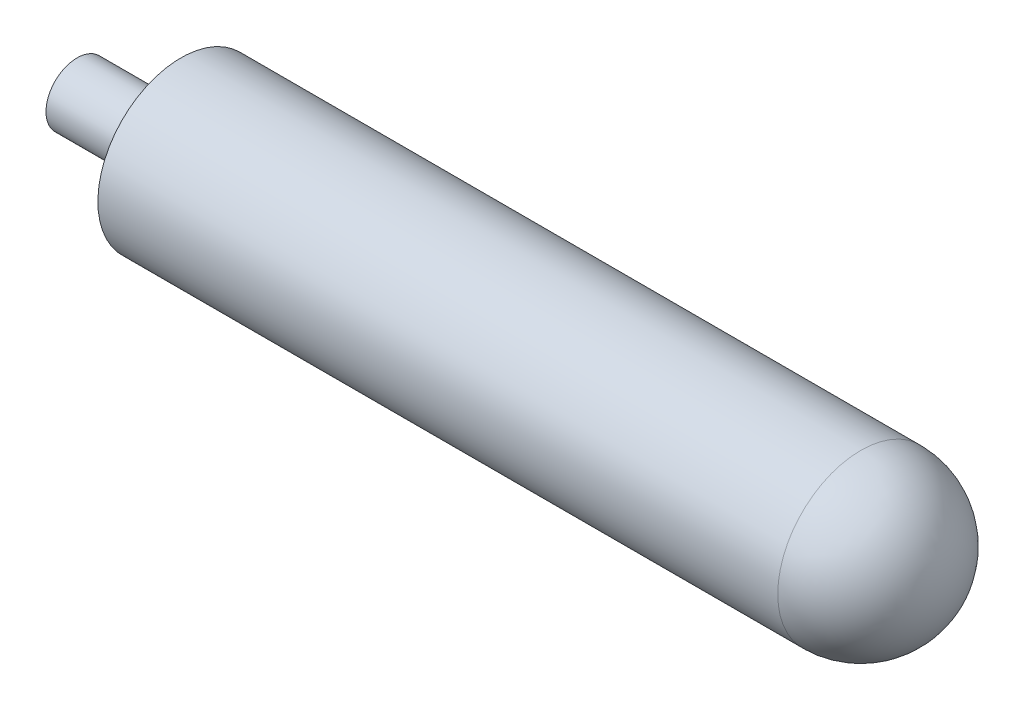
SolidWorks part; units mm, degrees
ref_plane "Front Plane" through (0, 0, 0) normal (0, 0, 1) x (1, 0, 0)
ref_plane "Top Plane" through (0, 0, 0) normal (0, 1, 0) x (1, 0, 0)
ref_plane "Right Plane" through (0, 0, 0) normal (1, 0, 0) x (0, 0, -1)
sketch "Sketch1" plane through (0, 0, 0) normal (0, 0, 1) x (1, 0, 0)
  line L0 (0, 0) -> (68, 0) construction
  line L1 (6.5, 0) -> (6.5, 3)
  line L2 (6.5, 3) -> (16.5, 3)
  line L3 (16.5, 3) -> (16.5, 8)
  line L4 (16.5, 8) -> (68, 8)
  line L5 (68, 8) -> (68, 0)
  line L6 (6.5, 0) -> (68, 0) construction
  line L7 (6.5, 0) -> (68, 0)
  point P8 (6.5, 1.5)
  point P10 (67.5075, 0)
  dimension "D1" = 6.5
  dimension "D2" = 16.5
  dimension "D3" = 68
  dimension "D4" = 3
  dimension "D5" = 8
revolve "Revolve1" add sketch "Sketch1" angle 360 about L7
sketch "Sketch2" plane through (0, 0, 0) normal (0, 0, 1) x (1, 0, 0)
  line L0 (0, 0) -> (109.6147, 0) construction
  line L1 (68, 0) -> (68, 8)
  line L2 (68, 8) -> (16.5, 8) construction
  line L5 (68, 8) -> (82, 8)
  line L7 (68, 0) -> (90, 0)
  arc A1 (82, 8) -> (90, 0) centre (82, 0) cw
  dimension "D3" = 8
  dimension "D1" = 68
  dimension "D2" = 82
revolve "Revolve2" add sketch "Sketch2" angle 360 about L0
equation "\"TipBracket: Turret Offset\"= 16mm"
equation "\"TipBracket: Axle Diameter\"= 6mm"
equation "\"TipBracket: Bearing Outer Diameter\"= 13mm'686ZZ"
equation "\"TipBracket: Bearing Width\"= 5mm'686ZZ"
equation "\"TipBracket: Bracket Thickness\"= 4mm"
equation "\"TipBracket: Socket Outer\"= \"Bracket: Arm Gap\" + 2 * \"Bracket: Clamp Wall\""
equation "\"TipBracket: Socket Cap\"= 3mm"
equation "\"TipBracket: Bearing Housing Wall Thicknes\"= 2.5mm"
equation "\"TipBracket: Bearing Boss Diameter\"= \"TipBracket: Bearing Outer Diameter\" + 2 * \"TipBracket: Bearing Housing Wall Thicknes\""
equation "\"TipBracket: Socket-Axle Distance\"= \"Bracket: Clamp Length\" + \"TipBracket: Bearing Boss Diameter\" / 2"
equation "\"Bracket: Arm Size\"= 10mm"
equation "\"Bracket: Arm Gap\"= \"Bracket: Arm Size\" + 0.2mm"
equation "\"Bracket: Clamp Wall\"= 2.5mm"
equation "\"Bracket: Clamp Length\"= 8mm"
equation "\"Axle: Hub Width\"= 14mm"
equation "\"Axle: Hub Overhang\"= 2mm"
equation "\"Axle: Drive Stickout\"= 15mm"
equation "\"Axle: Length\"= \"TipBracket: Turret Offset\" + \"Axle: Hub Width\" / 2 + \"Axle: Hub Overhang\" + \"TipBracket: Socket Outer\" / 2 + \"Axle: Drive Stickout\""
equation "\"Axle: D-Flat Depth\"= 0.5mm"
equation "\"Hub: Spigot Diameter\"= 6mm"
equation "\"Hub: Spigot Hole\"= \"Hub: Spigot Diameter\" + 0.2mm"
equation "\"Hub: Socket Depth\"= 10mm"
equation "\"Hub: Socket Floor\"= 6.5mm"
equation "\"Hub: Diameter\"= 2 * ( \"Hub: Socket Depth\" + \"Hub: Socket Floor\" )"
equation "\"Hub: Set Screw Hole\"= 2.5mm"
equation "\"Hub: Head Count\"= 5"
equation "\"Head: Tip Radius\"= 90mm"
equation "\"Head: Body Diameter\"= 16mm"
equation "\"Head: Tuft Diameter\" = 16mm"
equation "\"Head: Tuft Length\"= 22mm"
equation "\"Head: Tuft Dome\"= \"Head: Tuft Diameter\" / 2"
equation "\"Head: Body End\"= \"Head: Tip Radius\" - \"Head: Tuft Length\""
equation "\"D1@Sketch1\"=\"Hub: Socket Floor\""
equation "\"D2@Sketch1\"=\"Hub: Diameter\"/2"
equation "\"D3@Sketch1\"=\"Head: Body End\""
equation "\"D4@Sketch1\"=\"Hub: Spigot Diameter\"/2"
equation "\"D5@Sketch1\"=\"Head: Body Diameter\"/2"
equation "\"D1@Sketch2\"=\"Head: Body End\""
equation "\"D2@Sketch2\"=\"Head: Tip Radius\" - \"Head: Tuft Dome\""
equation "\"D3@Sketch2\"=\"Head: Tuft Dome\""
